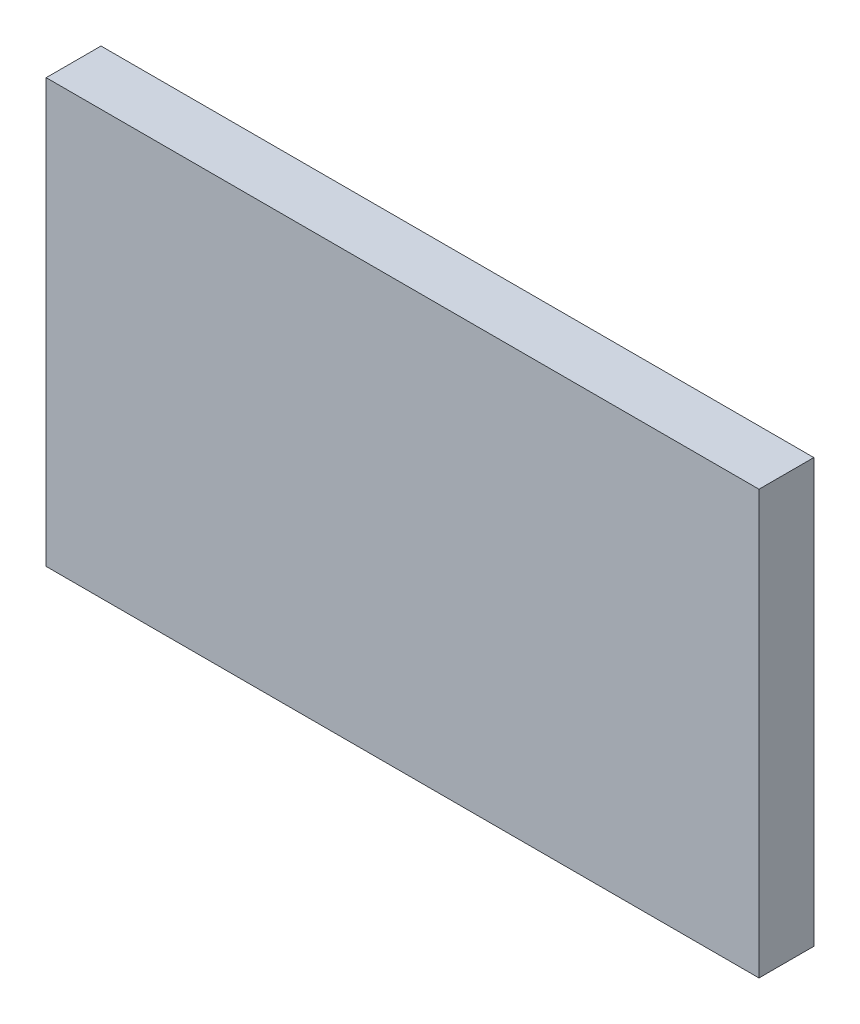
SolidWorks part; units mm, degrees
ref_plane "前视基准面" through (0, 0, 0) normal (0, 0, 1) x (1, 0, 0)
ref_plane "上视基准面" through (0, 0, 0) normal (0, 1, 0) x (1, 0, 0)
ref_plane "右视基准面" through (0, 0, 0) normal (1, 0, 0) x (0, 0, -1)
sketch "草图1" plane through (0, 0, 0) normal (0, 0, 1) x (1, 0, 0)
  line L1 (162.5, 96.5) -> (-162.5, 96.5)
  line L2 (162.5, 96.5) -> (162.5, -96.5)
  line L3 (162.5, -96.5) -> (-162.5, -96.5)
  line L4 (-162.5, 96.5) -> (-162.5, -96.5)
  line L5 (0, -96.5) -> (0, 96.5) construction
  line L6 (162.5, 0) -> (-162.5, 0) construction
  point P0 (0, 0)
  dimension "D1" = 325
  dimension "D2" = 193
extrude "凸台-拉伸1" add sketch "草图1" along normal blind 25 contours L1 L4 L3 L2
sketch "草图2" plane through (0, 0, 25) normal (0, 0, 1) x (1, 0, 0)
  line L1 (-145, 85) -> (145, 85)
  line L2 (-145, 85) -> (-145, -85)
  line L3 (-145, -85) -> (145, -85)
  line L4 (145, 85) -> (145, -85)
  line L5 (0, -85) -> (0, 85) construction
  line L6 (-145, 0) -> (145, 0) construction
  point P0 (0, 0)
  dimension "D1" = 290
  dimension "D2" = 170
